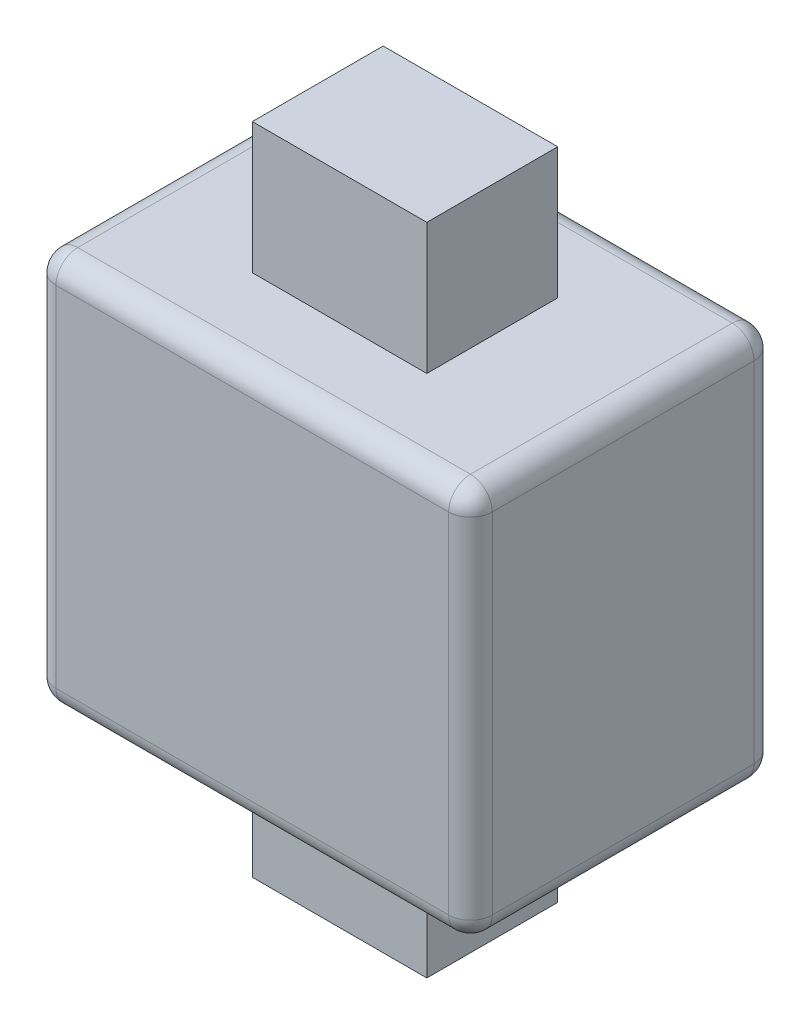
SolidWorks part; units mm, degrees
ref_plane "Front Plane" through (0, 0, 0) normal (0, 0, 1) x (1, 0, 0)
ref_plane "Top Plane" through (0, 0, 0) normal (0, 1, 0) x (1, 0, 0)
ref_plane "Right Plane" through (0, 0, 0) normal (1, 0, 0) x (0, 0, -1)
sketch "Sketch1" plane through (0, 0, 0) normal (0, 0, 1) x (1, 0, 0)
  line L1 (-2.5, 2.25) -> (2.5, 2.25)
  line L2 (-2.5, 2.25) -> (-2.5, -2.25)
  line L3 (-2.5, -2.25) -> (2.5, -2.25)
  line L4 (2.5, 2.25) -> (2.5, -2.25)
  line L5 (-2.5, 2.25) -> (2.5, -2.25) construction
  line L6 (-2.5, -2.25) -> (2.5, 2.25) construction
  point P0 (0, 0)
  dimension "D1" = 5
  dimension "D2" = 4.5
extrude "Boss-Extrude1" add sketch "Sketch1" along normal blind 3.5
sketch "Sketch2" plane through (0, 2.25, 0) normal (0, 1, 0) x (1, 0, 0)
  line L0 (2.5, 0) -> (-2.5, -3.5)
  line L2 (1, -2.5) -> (-1, -2.5)
  line L3 (1, -2.5) -> (1, -1)
  line L4 (1, -1) -> (-1, -1)
  line L5 (-1, -2.5) -> (-1, -1)
  line L6 (1, -2.5) -> (-1, -1) construction
  line L7 (1, -1) -> (-1, -2.5) construction
  point P4 (0, -1.75)
  dimension "D1" = 1.5
  dimension "D2" = 2
extrude "Boss-Extrude2" add sketch "Sketch2" along normal blind 1.5 contours L5 L0 L3 L4 | L5 L2 L3 L0
sketch "Sketch3" plane through (0, -2.25, 0) normal (0, -1, 0) x (-1, 0, 0)
  line L0 (-2.5, -3.5) -> (2.5, 0)
  line L2 (1, -2.5) -> (-1, -2.5)
  line L3 (1, -2.5) -> (1, -1)
  line L4 (1, -1) -> (-1, -1)
  line L5 (-1, -2.5) -> (-1, -1)
  line L6 (1, -2.5) -> (-1, -1) construction
  line L7 (1, -1) -> (-1, -2.5) construction
  point P4 (0, -1.75)
  dimension "D1" = 1.5
  dimension "D2" = 2
extrude "Boss-Extrude3" add sketch "Sketch3" along normal blind 1.5 contours L5 L0 L3 L4 | L5 L2 L3 L0
fillet "Fillet1" radius 0.25 12 edges at (-2.5, -2.25, 1.75) (0, -2.25, 3.5) (2.5, -2.25, 1.75) (0, -2.25, 0) (2.5, 0, 0) (-2.5, 0, 0) (2.5, 0, 3.5) (-2.5, 0, 3.5) (0, 2.25, 0) (-2.5, 2.25, 1.75) (2.5, 2.25, 1.75) (0, 2.25, 3.5)
sketch "Sketch4" plane through (0, 0, 0) normal (0, 0, -1) x (-1, 0, 0)
  line L0 (0, -2) -> (0, 2)
  line L1 (-2.25, -2) -> (2.25, -2) construction
  line L2 (2.25, 2) -> (-2.25, 2) construction
  line L3 (-2.25, 0) -> (2.25, 0)
  line L4 (-2.25, 2) -> (-2.25, -2) construction
  line L5 (2.25, -2) -> (2.25, 2) construction
